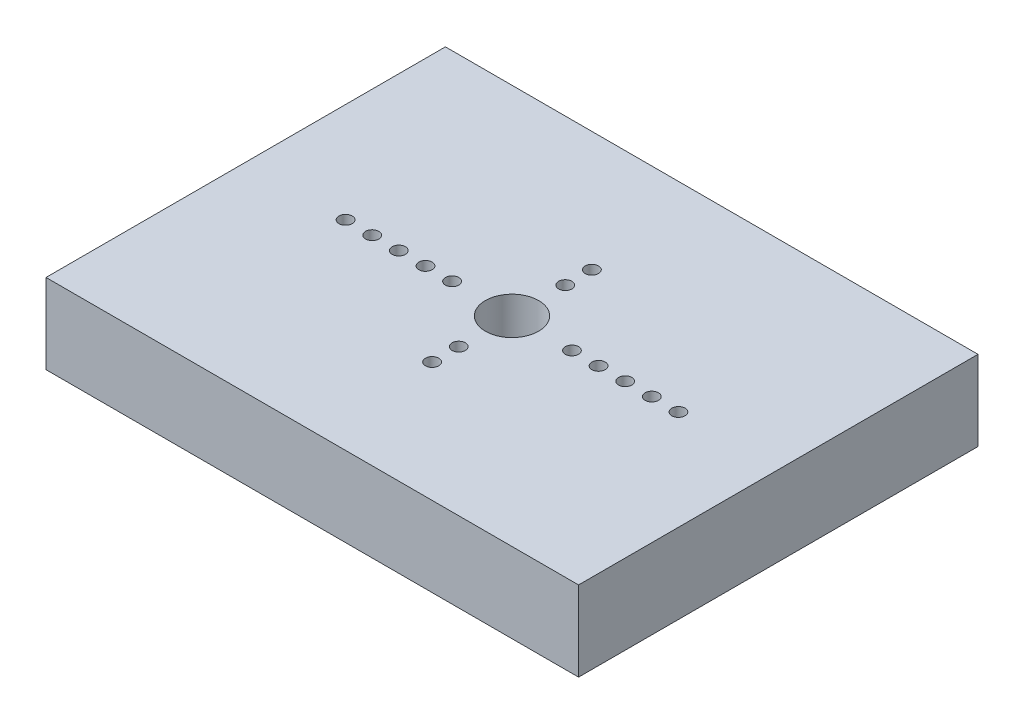
SolidWorks part; units mm, degrees
ref_plane "Front Plane" through (0, 0, 0) normal (0, 0, 1) x (1, 0, 0)
ref_plane "Top Plane" through (0, 0, 0) normal (0, 1, 0) x (1, 0, 0)
ref_plane "Right Plane" through (0, 0, 0) normal (1, 0, 0) x (0, 0, -1)
sketch "Sketch1" plane through (0, 0, 0) normal (0, 1, 0) x (1, 0, 0)
  line L0 (-2.55, -2.55) -> (-2.55, -7.85)
  line L1 (-2.55, 7.85) -> (2.55, 7.85)
  line L2 (-2.55, 7.85) -> (-2.55, 2.55)
  line L3 (-2.55, -7.85) -> (2.55, -7.85)
  line L4 (2.55, 7.85) -> (2.55, 2.55)
  line L5 (-2.55, 7.85) -> (2.55, -7.85) construction
  line L6 (-2.55, -7.85) -> (2.55, 7.85) construction
  line L7 (-14.5, -2.55) -> (-2.55, -2.55)
  line L8 (-14.5, -2.55) -> (-14.5, 2.55)
  line L9 (-14.5, 2.55) -> (-2.55, 2.55)
  line L10 (14.5, -2.55) -> (14.5, 2.55)
  line L11 (-14.5, -2.55) -> (14.5, 2.55) construction
  line L12 (-14.5, 2.55) -> (14.5, -2.55) construction
  line L13 (2.55, -2.55) -> (14.5, -2.55)
  line L14 (2.55, -2.55) -> (2.55, -7.85)
  line L15 (2.55, 2.55) -> (14.5, 2.55)
  line L17 (20, -15) -> (-20, -15)
  line L18 (20, -15) -> (20, 15)
  line L19 (20, 15) -> (-20, 15)
  line L20 (-20, -15) -> (-20, 15)
  line L21 (20, -15) -> (-20, 15) construction
  line L22 (20, 15) -> (-20, -15) construction
  point P0 (0, 0)
  point P5 (0, 0)
  point P15 (0, 0)
  dimension "D1" = 5.1
  dimension "D2" = 15.7
  dimension "D3" = 5.1
  dimension "D4" = 29
  dimension "D5" = 40
  dimension "D6" = 30
extrude "Boss-Extrude1" add sketch "Sketch1" along normal blind 3
sketch "Sketch2" plane through (0, 3, 0) normal (0, 1, 0) x (1, 0, 0)
  line L0 (-20, 15) -> (-20, -15)
  line L1 (-20, -15) -> (20, -15)
  line L2 (20, -15) -> (20, 15)
  line L3 (20, 15) -> (-20, 15)
  line L4 (-14.5, 0) -> (14.5, 0) construction
  line L5 (-14.5, 2.55) -> (-14.5, -2.55) construction
  line L6 (14.5, -2.55) -> (14.5, 2.55) construction
  line L7 (0, 7.85) -> (0, -7.85) construction
  line L8 (2.55, 7.85) -> (-2.55, 7.85) construction
  line L9 (-2.55, -7.85) -> (2.55, -7.85) construction
  circle A0 centre (0, 0) radius 2
  circle A1 centre (-4.5, 0) radius 0.5
  circle A2 centre (-6.5, 0) radius 0.5
  circle A3 centre (-8.5, 0) radius 0.5
  circle A4 centre (-10.5, 0) radius 0.5
  circle A5 centre (-12.5, 0) radius 0.5
  circle A6 centre (0, 4) radius 0.5
  circle A7 centre (0, 6) radius 0.5
  circle A8 centre (12.5, 0) radius 0.5
  circle A9 centre (10.5, 0) radius 0.5
  circle A10 centre (8.5, 0) radius 0.5
  circle A11 centre (6.5, 0) radius 0.5
  circle A12 centre (4.5, 0) radius 0.5
  circle A13 centre (0, -4) radius 0.5
  circle A14 centre (0, -6) radius 0.5
  dimension "D1" = 4
  dimension "D2" = 4.5
  dimension "D3" = 1
  dimension "D5" = 2
  dimension "D6" = 4
  dimension "D7" = 2
  dimension "D4" = 5
extrude "Boss-Extrude2" add sketch "Sketch2" along normal blind 3
